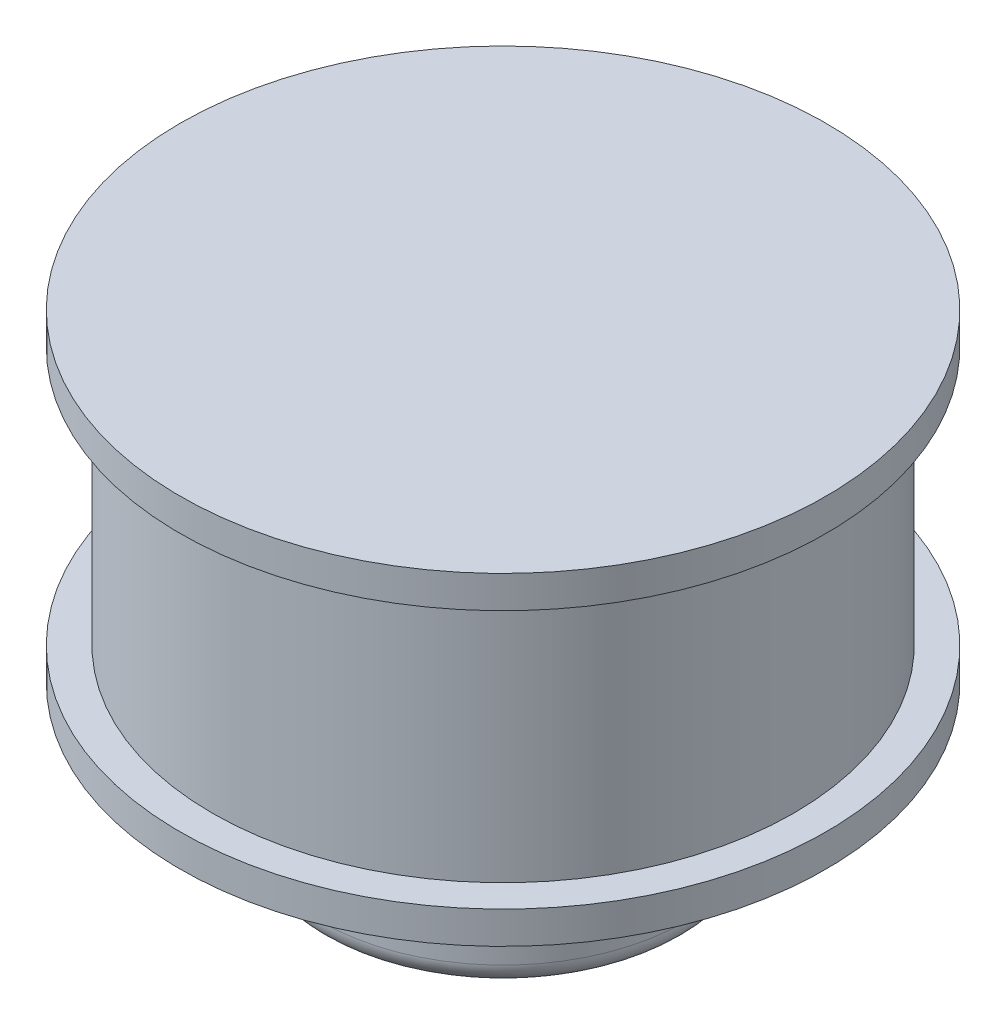
SolidWorks part; units mm, degrees
material "ABS"
ref_plane "Front Plane" through (0, 0, 0) normal (0, 0, 1) x (1, 0, 0)
ref_plane "Top Plane" through (0, 0, 0) normal (0, 1, 0) x (1, 0, 0)
ref_plane "Right Plane" through (0, 0, 0) normal (1, 0, 0) x (0, 0, -1)
sketch "Sketch1" plane through (0, 0, 0) normal (0, 0, 1) x (1, 0, 0)
  line L2 (-8.5, -6.35) -> (-8.5, 0)
  line L3 (-8.5, 0) -> (-15, 0)
  line L4 (-15, 0) -> (-15, 1.5)
  line L5 (-15, 1.5) -> (-13.5, 1.5)
  line L6 (-13.5, 1.5) -> (-13.5, 13.5)
  line L7 (-13.5, 13.5) -> (-15, 13.5)
  line L8 (-15, 13.5) -> (-15, 15)
  line L9 (-15, 15) -> (0, 15)
  line L10 (0, 15) -> (0, 7.65)
  line L11 (-4, -6.35) -> (-8.5, -6.35)
  line L12 (-4, 7.65) -> (-4, -6.35)
  line L13 (0, 7.65) -> (-4, 7.65)
  dimension "D1" = 8.5
  dimension "D2" = 1.5
  dimension "D3" = 6.35
  dimension "D4" = 1.5
  dimension "D5" = 4
  dimension "D6" = 14
  dimension "D7" = 15
  dimension "D8" = 15
revolve "Revolve1" add sketch "Sketch1" angle 360 about L10
fillet "Fillet1" radius 1 2 edges at (-8.5, -6.35, 0) (-4, -6.35, 0)
hole_wizard "M3x0.5 Tapped Hole1" positions "Sketch2" profile "Sketch3" tap size "M3x0.5" standard "ANSI Metric"
sketch "Sketch2" plane through (0, 0, 0) normal (0, 0, 1) x (1, 0, 0)
  line L0 (-7.5, -6.35) -> (7.5, -6.35) construction
  point P0 (0, -2.35)
  dimension "D1" = 4
sketch "Sketch3" plane through (0, -2.35, 0) normal (1, 0, 0) x (0, 1, 0)
  line L0 (0, 0) -> (0, 8.5)
  line L1 (0, 8.5) -> (1.25, 8.5)
  line L2 (1.25, 8.5) -> (1.25, 0)
  line L5 (1.25, 0) -> (0, 0)
  line L11 (0, -6.35) -> (0, 107.95) construction
  dimension "Thru Tap Drill Dia." = 2.5
  dimension "Thru Tap Drill Depth" = 8.5
cosmetic thread "Hole Thread1" parameters "D2"=3
